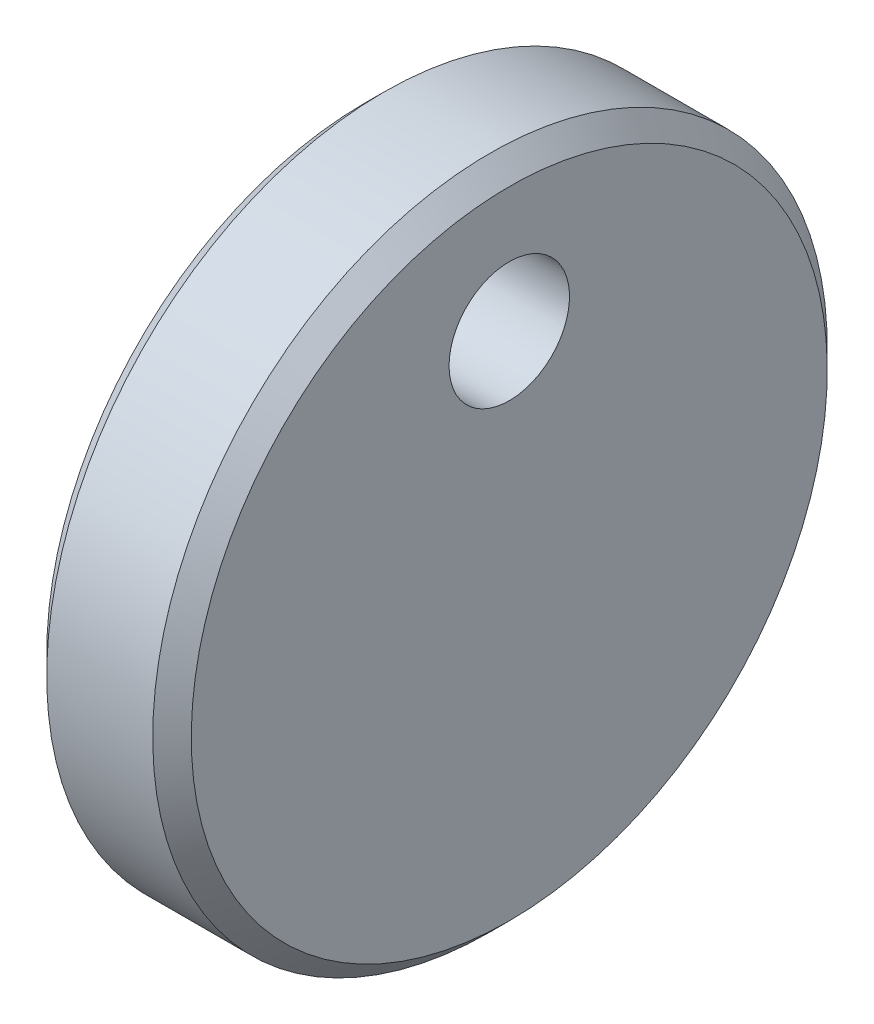
SolidWorks part; units mm, degrees
material "2024 Сплав"
ref_plane "Спереди" through (0, 0, 0) normal (0, 0, 1) x (1, 0, 0)
ref_plane "Сверху" through (0, 0, 0) normal (0, 1, 0) x (1, 0, 0)
ref_plane "Справа" through (0, 0, 0) normal (1, 0, 0) x (0, 0, -1)
sketch "Эскиз2" plane through (0, 0, 0) normal (0, 0, 1) x (1, 0, 0)
  line L0 (0, 0) -> (0, 7)
  line L1 (0, 7) -> (-3, 7)
  line L2 (-3, 7) -> (-3, 0)
  line L5 (-3, 0) -> (0, 0) construction
  line L6 (0, 0) -> (-3, 0)
  dimension "D2" = 3
  dimension "D4" = 7
revolve "Повернуть1" add sketch "Эскиз2" angle 360 about L5
sketch "Эскиз3" plane through (-3, 0, 0) normal (-1, 0, 0) x (0, 0, 1)
  circle A0 centre (0, 4) radius 1.25
  dimension "D1" = 2.5
  dimension "D2" = 4
extrude "Вырез-Вытянуть1" cut sketch "Эскиз3" against normal through all contours A0
chamfer "Фаска1" distance 0.4 angle 45 2 edges at (0, -7, 0) (-3, -7, 0)
